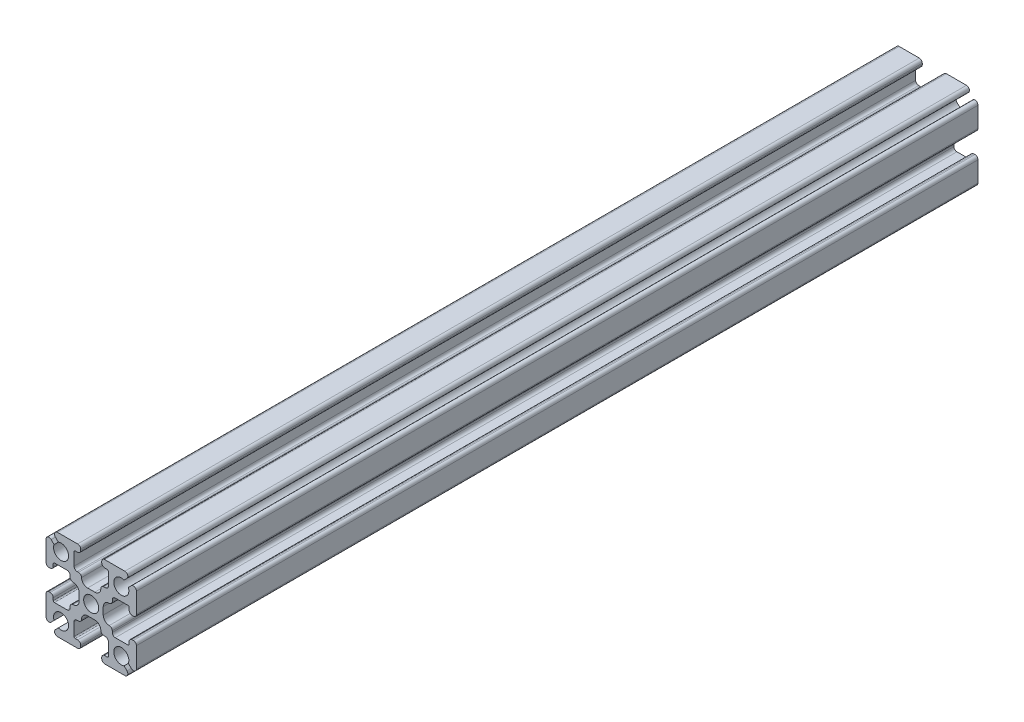
SolidWorks part; units mm, degrees
ref_plane "Front Plane" through (0, 0, 0) normal (0, 0, 1) x (1, 0, 0)
ref_plane "Top Plane" through (0, 0, 0) normal (0, 1, 0) x (1, 0, 0)
ref_plane "Right Plane" through (0, 0, 0) normal (1, 0, 0) x (0, 0, -1)
sketch "Sketch1" plane through (0, 0, 0) normal (0, 0, 1) x (1, 0, 0)
  line L0 (6.6464, 5.9393) -> (6.1636, 5.4565)
  line L1 (5.4565, 6.1636) -> (5.9393, 6.6464)
  line L2 (5.5858, 7.5) -> (2.25, 7.5)
  line L3 (1.75, 7) -> (1.75, 6.8)
  line L4 (2.25, 6.3) -> (2.65, 6.3)
  line L5 (2.85, 6.1) -> (2.85, 4)
  line L6 (2.35, 3.5) -> (2.1, 3.5)
  line L7 (0.6, 2) -> (-0.6, 2)
  line L8 (-2.1, 3.5) -> (-2.35, 3.5)
  line L9 (-2.85, 4) -> (-2.85, 6.1)
  line L10 (-2.65, 6.3) -> (-2.25, 6.3)
  line L11 (-1.75, 6.8) -> (-1.75, 7)
  line L12 (-2.25, 7.5) -> (-5.5858, 7.5)
  line L13 (-5.9393, 6.6464) -> (-5.4565, 6.1636)
  line L14 (-6.1636, 5.4565) -> (-6.6464, 5.9393)
  line L15 (-7.5, 5.5858) -> (-7.5, 2.25)
  line L16 (-7, 1.75) -> (-6.8, 1.75)
  line L17 (-6.3, 2.25) -> (-6.3, 2.65)
  line L18 (-6.1, 2.85) -> (-4, 2.85)
  line L19 (-3.5, 2.35) -> (-3.5, 2.1)
  line L20 (-2, 0.6) -> (-2, -0.6)
  line L21 (-3.5, -2.1) -> (-3.5, -2.35)
  line L22 (-4, -2.85) -> (-6.1, -2.85)
  line L23 (-6.3, -2.65) -> (-6.3, -2.25)
  line L24 (-6.8, -1.75) -> (-7, -1.75)
  line L25 (-7.5, -2.25) -> (-7.5, -5.5858)
  line L26 (-6.6464, -5.9393) -> (-6.1636, -5.4565)
  line L27 (-5.4565, -6.1636) -> (-5.9393, -6.6464)
  line L28 (-5.5858, -7.5) -> (-2.25, -7.5)
  line L29 (-1.75, -7) -> (-1.75, -6.8)
  line L30 (-2.25, -6.3) -> (-2.65, -6.3)
  line L31 (-2.85, -6.1) -> (-2.85, -4)
  line L32 (-2.35, -3.5) -> (-2.1, -3.5)
  line L33 (-0.6, -2) -> (0.6, -2)
  line L34 (2.1, -3.5) -> (2.35, -3.5)
  line L35 (2.85, -4) -> (2.85, -6.1)
  line L36 (2.65, -6.3) -> (2.25, -6.3)
  line L37 (1.75, -6.8) -> (1.75, -7)
  line L38 (2.25, -7.5) -> (5.5858, -7.5)
  line L39 (5.9393, -6.6464) -> (5.4565, -6.1636)
  line L40 (6.1636, -5.4565) -> (6.6464, -5.9393)
  line L41 (7.5, -5.5858) -> (7.5, -2.25)
  line L42 (7, -1.75) -> (6.8, -1.75)
  line L43 (6.3, -2.25) -> (6.3, -2.65)
  line L44 (6.1, -2.85) -> (4, -2.85)
  line L45 (3.5, -2.35) -> (3.5, -2.1)
  line L46 (2, -0.6) -> (2, 0.6)
  line L47 (3.5, 2.1) -> (3.5, 2.35)
  line L48 (4, 2.85) -> (6.1, 2.85)
  line L49 (6.3, 2.65) -> (6.3, 2.25)
  line L50 (6.8, 1.75) -> (7, 1.75)
  line L51 (7.5, 2.25) -> (7.5, 5.5858)
  circle A0 centre (0, 0) radius 1.25
  arc A1 (6.1636, 5.4565) -> (5.4565, 6.1636) centre (5, 5) cw
  arc A2 (5.9393, 6.6464) -> (5.5858, 7.5) centre (5.5858, 7) ccw
  arc A3 (2.25, 7.5) -> (1.75, 7) centre (2.25, 7) ccw
  arc A4 (1.75, 6.8) -> (2.25, 6.3) centre (2.25, 6.8) ccw
  arc A5 (2.65, 6.3) -> (2.85, 6.1) centre (2.65, 6.1) cw
  arc A6 (2.85, 4) -> (2.35, 3.5) centre (2.35, 4) cw
  arc A7 (2.1, 3.5) -> (1.6, 3) centre (2.1, 3) ccw
  arc A8 (1.6, 3) -> (0.6, 2) centre (0.6, 3) cw
  arc A9 (-0.6, 2) -> (-1.6, 3) centre (-0.6, 3) cw
  arc A10 (-1.6, 3) -> (-2.1, 3.5) centre (-2.1, 3) ccw
  arc A11 (-2.35, 3.5) -> (-2.85, 4) centre (-2.35, 4) cw
  arc A12 (-2.85, 6.1) -> (-2.65, 6.3) centre (-2.65, 6.1) cw
  arc A13 (-2.25, 6.3) -> (-1.75, 6.8) centre (-2.25, 6.8) ccw
  arc A14 (-1.75, 7) -> (-2.25, 7.5) centre (-2.25, 7) ccw
  arc A15 (-5.5858, 7.5) -> (-5.9393, 6.6464) centre (-5.5858, 7) ccw
  arc A16 (-5.4565, 6.1636) -> (-6.1636, 5.4565) centre (-5, 5) cw
  arc A17 (-6.6464, 5.9393) -> (-7.5, 5.5858) centre (-7, 5.5858) ccw
  arc A18 (-7.5, 2.25) -> (-7, 1.75) centre (-7, 2.25) ccw
  arc A19 (-6.8, 1.75) -> (-6.3, 2.25) centre (-6.8, 2.25) ccw
  arc A20 (-6.3, 2.65) -> (-6.1, 2.85) centre (-6.1, 2.65) cw
  arc A21 (-4, 2.85) -> (-3.5, 2.35) centre (-4, 2.35) cw
  arc A22 (-3.5, 2.1) -> (-3, 1.6) centre (-3, 2.1) ccw
  arc A23 (-3, 1.6) -> (-2, 0.6) centre (-3, 0.6) cw
  arc A24 (-2, -0.6) -> (-3, -1.6) centre (-3, -0.6) cw
  arc A25 (-3, -1.6) -> (-3.5, -2.1) centre (-3, -2.1) ccw
  arc A26 (-3.5, -2.35) -> (-4, -2.85) centre (-4, -2.35) cw
  arc A27 (-6.1, -2.85) -> (-6.3, -2.65) centre (-6.1, -2.65) cw
  arc A28 (-6.3, -2.25) -> (-6.8, -1.75) centre (-6.8, -2.25) ccw
  arc A29 (-7, -1.75) -> (-7.5, -2.25) centre (-7, -2.25) ccw
  arc A30 (-7.5, -5.5858) -> (-6.6464, -5.9393) centre (-7, -5.5858) ccw
  arc A31 (-6.1636, -5.4565) -> (-5.4565, -6.1636) centre (-5, -5) cw
  arc A32 (-5.9393, -6.6464) -> (-5.5858, -7.5) centre (-5.5858, -7) ccw
  arc A33 (-2.25, -7.5) -> (-1.75, -7) centre (-2.25, -7) ccw
  arc A34 (-1.75, -6.8) -> (-2.25, -6.3) centre (-2.25, -6.8) ccw
  arc A35 (-2.65, -6.3) -> (-2.85, -6.1) centre (-2.65, -6.1) cw
  arc A36 (-2.85, -4) -> (-2.35, -3.5) centre (-2.35, -4) cw
  arc A37 (-2.1, -3.5) -> (-1.6, -3) centre (-2.1, -3) ccw
  arc A38 (-1.6, -3) -> (-0.6, -2) centre (-0.6, -3) cw
  arc A39 (0.6, -2) -> (1.6, -3) centre (0.6, -3) cw
  arc A40 (1.6, -3) -> (2.1, -3.5) centre (2.1, -3) ccw
  arc A41 (2.35, -3.5) -> (2.85, -4) centre (2.35, -4) cw
  arc A42 (2.85, -6.1) -> (2.65, -6.3) centre (2.65, -6.1) cw
  arc A43 (2.25, -6.3) -> (1.75, -6.8) centre (2.25, -6.8) ccw
  arc A44 (1.75, -7) -> (2.25, -7.5) centre (2.25, -7) ccw
  arc A45 (5.5858, -7.5) -> (5.9393, -6.6464) centre (5.5858, -7) ccw
  arc A46 (5.4565, -6.1636) -> (6.1636, -5.4565) centre (5, -5) cw
  arc A47 (6.6464, -5.9393) -> (7.5, -5.5858) centre (7, -5.5858) ccw
  arc A48 (7.5, -2.25) -> (7, -1.75) centre (7, -2.25) ccw
  arc A49 (6.8, -1.75) -> (6.3, -2.25) centre (6.8, -2.25) ccw
  arc A50 (6.3, -2.65) -> (6.1, -2.85) centre (6.1, -2.65) cw
  arc A51 (4, -2.85) -> (3.5, -2.35) centre (4, -2.35) cw
  arc A52 (3.5, -2.1) -> (3, -1.6) centre (3, -2.1) ccw
  arc A53 (3, -1.6) -> (2, -0.6) centre (3, -0.6) cw
  arc A54 (2, 0.6) -> (3, 1.6) centre (3, 0.6) cw
  arc A55 (3, 1.6) -> (3.5, 2.1) centre (3, 2.1) ccw
  arc A56 (3.5, 2.35) -> (4, 2.85) centre (4, 2.35) cw
  arc A57 (6.1, 2.85) -> (6.3, 2.65) centre (6.1, 2.65) cw
  arc A58 (6.3, 2.25) -> (6.8, 1.75) centre (6.8, 2.25) ccw
  arc A59 (7, 1.75) -> (7.5, 2.25) centre (7, 2.25) ccw
  arc A60 (7.5, 5.5858) -> (6.6464, 5.9393) centre (7, 5.5858) ccw
extrude "Boss-Extrude1" add sketch "Sketch1" along normal blind 139.7
